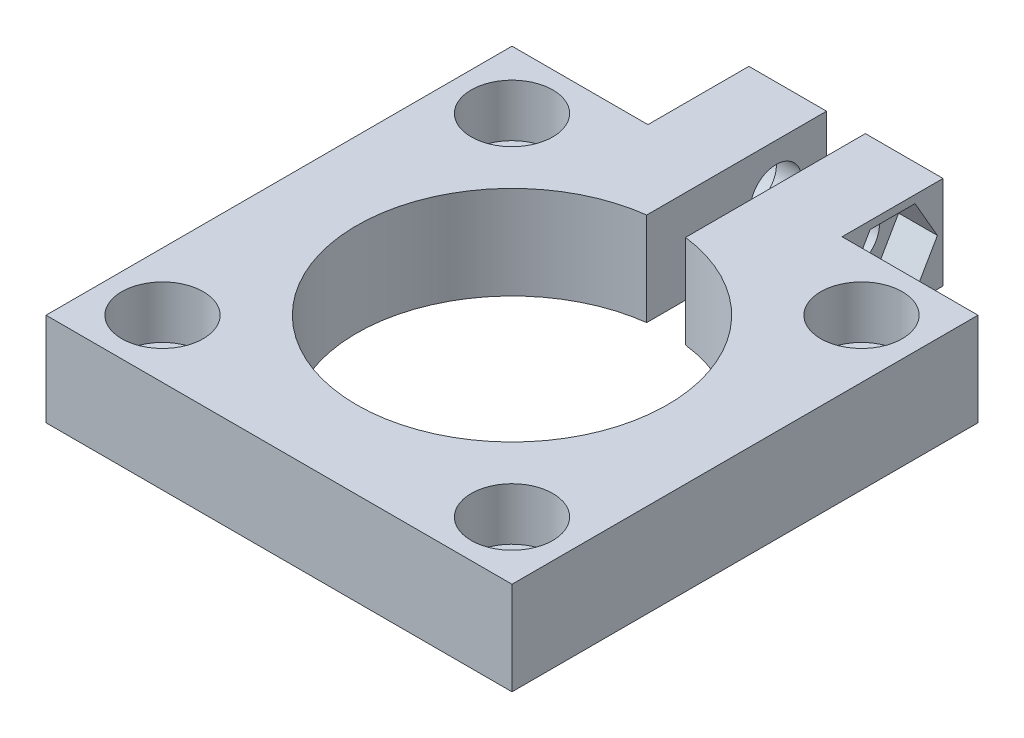
SolidWorks part; units mm, degrees
ref_plane "Front Plane" through (0, 0, 0) normal (0, 0, 1) x (1, 0, 0)
ref_plane "Top Plane" through (0, 0, 0) normal (0, 1, 0) x (1, 0, 0)
ref_plane "Right Plane" through (0, 0, 0) normal (1, 0, 0) x (0, 0, -1)
sketch "Sketch1" plane through (0, 0, 0) normal (0, 1, 0) x (1, 0, 0)
  line L1 (-30, 30) -> (30, 30)
  line L2 (-30, 30) -> (-30, -30)
  line L3 (-30, -30) -> (30, -30)
  line L4 (30, 30) -> (30, -30)
  line L5 (-30, 30) -> (30, -30) construction
  line L6 (-30, -30) -> (30, 30) construction
  point P0 (0, 0)
  dimension "D1" = 60
  dimension "D2" = 60
extrude "Boss-Extrude1" add sketch "Sketch1" along normal blind 12
sketch "Sketch3" plane through (0, 12, 0) normal (0, 1, 0) x (-1, 0, 0)
  circle A0 centre (0, 0) radius 20
extrude "Cut-Extrude1" cut sketch "Sketch3" against normal blind 12
sketch "Sketch4" plane through (0, 12, 0) normal (0, 1, 0) x (-1, 0, 0)
  line L0 (-30, -30) -> (30, -30) construction
  line L1 (2.5, -42.5) -> (-2.5, -42.5)
  line L2 (2.5, -42.5) -> (2.5, -17.5)
  line L3 (2.5, -17.5) -> (-2.5, -17.5)
  line L4 (-2.5, -42.5) -> (-2.5, -17.5)
  line L5 (2.5, -42.5) -> (-2.5, -17.5) construction
  line L6 (2.5, -17.5) -> (-2.5, -42.5) construction
  point P0 (0, -30)
  dimension "D1" = 25
extrude "Cut-Extrude2" cut sketch "Sketch4" against normal blind 12
sketch "Sketch5" plane through (0, 12, 0) normal (0, 1, 0) x (-1, 0, 0)
  line L1 (2.5, -30) -> (12.5, -30)
  line L2 (2.5, -30) -> (2.5, -43)
  line L3 (2.5, -43) -> (12.5, -43)
  line L4 (12.5, -30) -> (12.5, -43)
  dimension "D1" = 13
  dimension "D2" = 10
extrude "Boss-Extrude4" add sketch "Sketch5" against normal blind 12
pattern_linear "LPattern1" count 2 spacing 15 along (1, 0, 0) of "Boss-Extrude4"
hole_wizard "CBORE for M6 Hex Socket Head Cap Screw1" positions "Sketch7" profile "Sketch6" counterbore size "M6" standard "DIN" end condition through all
sketch "Sketch7" plane through (-12.5, 0, 0) normal (-1, 0, 0) x (0, 0, 1)
  line L0 (-43, 0) -> (-30, 0) construction
  line L1 (-43, 0) -> (-43, 12) construction
  point P0 (-36.5, 6)
  point P10 (-36.5, 0)
  point P11 (-43, 6)
  dimension "D1" = 0
  dimension "D2" = 0
sketch "Sketch6" plane through (-12.5, 6, -36.5) normal (0, 1, 0) x (0, 0, 1)
  line L0 (0, 0) -> (0, 42.5)
  line L1 (0, 42.5) -> (3.3, 42.5)
  line L3 (3.3, 42.5) -> (3.3, 6.75)
  line L4 (3.3, 6.75) -> (5.25, 6.75)
  line L5 (5.25, 6.75) -> (5.25, 0)
  line L7 (5.25, 0) -> (0, 0)
  line L11 (0, -6.35) -> (0, 107.95) construction
  dimension "Thru Hole Dia." = 6.6
  dimension "Thru Hole Depth" = 42.5
  dimension "C'Bore Dia." = 10.5
  dimension "C'Bore Depth" = 6.75
sketch "Sketch9" plane through (12.5, 0, 0) normal (1, 0, 0) x (0, 0, -1)
  line L0 (30, 0) -> (43, 0) construction
  line L1 (42.2735, 6) -> (39.3868, 11)
  line L2 (39.3868, 11) -> (33.6132, 11)
  line L3 (33.6132, 11) -> (30.7265, 6)
  line L4 (30.7265, 6) -> (33.6132, 1)
  line L5 (33.6132, 1) -> (39.3868, 1)
  line L6 (39.3868, 1) -> (42.2735, 6)
  line L8 (43, 0) -> (43, 12) construction
  circle A0 centre (36.5, 6) radius 5 construction
  point P1 (36.5, 0)
  point P11 (43, 6)
  dimension "D1" = 5
  dimension "D2" = 0
  dimension "D3" = 0
extrude "Cut-Extrude3" cut sketch "Sketch9" against normal blind 4.9902
hole_wizard "CBORE for M6 Hex Socket Head Cap Screw2" positions "Sketch11" profile "Sketch10" counterbore size "M6" standard "DIN" end condition through all
sketch "Sketch11" plane through (0, 12, 0) normal (0, 1, 0) x (-1, 0, 0)
  point P0 (22.5, -22.5)
  dimension "D1" = 22.5
  dimension "D2" = 22.5
sketch "Sketch10" plane through (-22.5, 12, -22.5) normal (1, 0, 0) x (0, 0, 1)
  line L0 (0, 0) -> (0, 12)
  line L1 (0, 12) -> (3.75, 12)
  line L3 (3.75, 12) -> (3.75, 6.75)
  line L4 (3.75, 6.75) -> (5.25, 6.75)
  line L5 (5.25, 6.75) -> (5.25, 0)
  line L7 (5.25, 0) -> (0, 0)
  line L11 (0, -6.35) -> (0, 107.95) construction
  dimension "Thru Hole Dia." = 7.5
  dimension "Thru Hole Depth" = 12
  dimension "C'Bore Dia." = 10.5
  dimension "C'Bore Depth" = 6.75
hole_wizard "CBORE for M6 Hex Socket Head Cap Screw3" positions "Sketch13" profile "Sketch12" counterbore size "M6" standard "DIN" end condition through all
sketch "Sketch13" plane through (0, 12, 0) normal (0, 1, 0) x (-1, 0, 0)
  point P0 (-22.5, -22.5)
  dimension "D1" = 22.5
  dimension "D2" = 22.5
sketch "Sketch12" plane through (22.5, 12, -22.5) normal (1, 0, 0) x (0, 0, 1)
  line L0 (0, 0) -> (0, 12)
  line L1 (0, 12) -> (3.75, 12)
  line L3 (3.75, 12) -> (3.75, 6.75)
  line L4 (3.75, 6.75) -> (5.25, 6.75)
  line L5 (5.25, 6.75) -> (5.25, 0)
  line L7 (5.25, 0) -> (0, 0)
  line L11 (0, -6.35) -> (0, 107.95) construction
  dimension "Thru Hole Dia." = 7.5
  dimension "Thru Hole Depth" = 12
  dimension "C'Bore Dia." = 10.5
  dimension "C'Bore Depth" = 6.75
hole_wizard "CBORE for M6 Hex Socket Head Cap Screw4" positions "Sketch15" profile "Sketch14" counterbore size "M6" standard "DIN" end condition through all
sketch "Sketch15" plane through (0, 12, 0) normal (0, 1, 0) x (-1, 0, 0)
  point P0 (-22.5, 22.5)
  dimension "D1" = 22.5
  dimension "D2" = 22.5
sketch "Sketch14" plane through (22.5, 12, 22.5) normal (1, 0, 0) x (0, 0, 1)
  line L0 (0, 0) -> (0, 12)
  line L1 (0, 12) -> (3.75, 12)
  line L3 (3.75, 12) -> (3.75, 6.75)
  line L4 (3.75, 6.75) -> (5.25, 6.75)
  line L5 (5.25, 6.75) -> (5.25, 0)
  line L7 (5.25, 0) -> (0, 0)
  line L11 (0, -6.35) -> (0, 107.95) construction
  dimension "Thru Hole Dia." = 7.5
  dimension "Thru Hole Depth" = 12
  dimension "C'Bore Dia." = 10.5
  dimension "C'Bore Depth" = 6.75
hole_wizard "CBORE for M6 Hex Socket Head Cap Screw5" positions "Sketch17" profile "Sketch16" counterbore size "M6" standard "DIN" end condition through all
sketch "Sketch17" plane through (0, 12, 0) normal (0, 1, 0) x (-1, 0, 0)
  point P0 (22.5, 22.5)
  dimension "D1" = 22.5
  dimension "D2" = 22.5
sketch "Sketch16" plane through (-22.5, 12, 22.5) normal (1, 0, 0) x (0, 0, 1)
  line L0 (0, 0) -> (0, 12)
  line L1 (0, 12) -> (3.75, 12)
  line L3 (3.75, 12) -> (3.75, 6.75)
  line L4 (3.75, 6.75) -> (5.25, 6.75)
  line L5 (5.25, 6.75) -> (5.25, 0)
  line L7 (5.25, 0) -> (0, 0)
  line L11 (0, -6.35) -> (0, 107.95) construction
  dimension "Thru Hole Dia." = 7.5
  dimension "Thru Hole Depth" = 12
  dimension "C'Bore Dia." = 10.5
  dimension "C'Bore Depth" = 6.75
